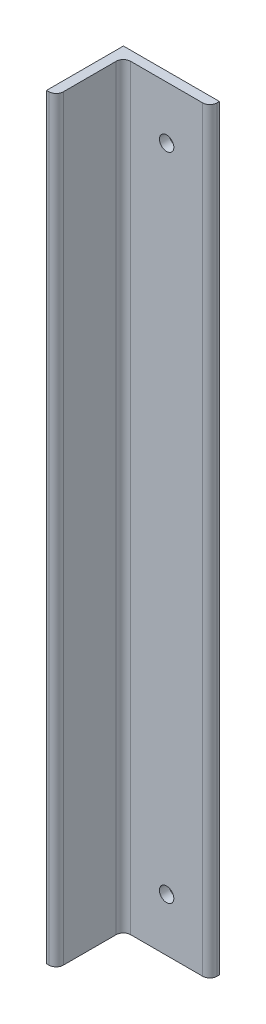
SolidWorks part; units mm, degrees
material "Aleación 6061"
ref_plane "Alzado" through (0, 0, 0) normal (0, 0, 1) x (1, 0, 0)
ref_plane "Planta" through (0, 0, 0) normal (0, 1, 0) x (1, 0, 0)
ref_plane "Vista lateral" through (0, 0, 0) normal (1, 0, 0) x (0, 0, -1)
sketch "Croquis1" plane through (0, 0, 0) normal (1, 0, 0) x (0, 0, -1)
  line L0 (0, 0) -> (0, 500)
  dimension "D1" = 500
other "Ángulo l L2.5X2X0.25(1)"
ref_plane "Plano1" through (0, 0, 0) normal (0, 1, 0) x (0, 0, 1)
sketch "Sketch1" plane through (0, 0, 0) normal (0, 1, 0) x (0, 0, 1)
  line L0 (0, 0) -> (0, 63.5)
  line L1 (0, 63.5) -> (1.5926, 63.5)
  line L2 (6.35, 58.7426) -> (6.35, 11.1125)
  line L3 (11.1125, 6.35) -> (46.0426, 6.35)
  line L4 (50.8, 1.5926) -> (50.8, 0)
  line L5 (50.8, 0) -> (0, 0)
  arc A0 (50.8, 1.5926) -> (46.0426, 6.35) centre (46.0426, 1.5926) ccw
  arc A1 (1.5926, 63.5) -> (6.35, 58.7426) centre (1.5926, 58.7426) cw
  arc A2 (11.1125, 6.35) -> (6.35, 11.1125) centre (11.1125, 11.1125) cw
  circle A3 centre (0, 0) radius 4.7625 construction
  point P10 (0, 31.75)
  point P14 (25.4, 0)
  point P15 (0, 0)
  dimension "D2" = 1.5926
  dimension "Radius_1" = 4.7625
  dimension "Radius_2" = 4.7625
  dimension "D1" = 6.35
  dimension "V_leg" = 63.5
  dimension "H_leg" = 50.8
  dimension "Thickness" = 6.35
  dimension "Flat_wid" = 1.5926
sketch "Croquis3" plane through (0, 0, 6.35) normal (0, 0, 1) x (1, 0, 0)
  line L0 (34.9275, 500) -> (34.9275, 0) construction
  line L1 (11.1125, 500) -> (58.7426, 500) construction
  line L2 (11.1125, 0) -> (58.7426, 0) construction
  circle A0 centre (34.9275, 465) radius 4.7625
  circle A1 centre (34.9275, 35) radius 4.7625
  dimension "D1" = 9.525
  dimension "D2" = 9.525
  dimension "D3" = 35
  dimension "D4" = 35
extrude "Cortar-Extruir1" cut sketch "Croquis3" against normal up to vertex (6.35 mm away)
